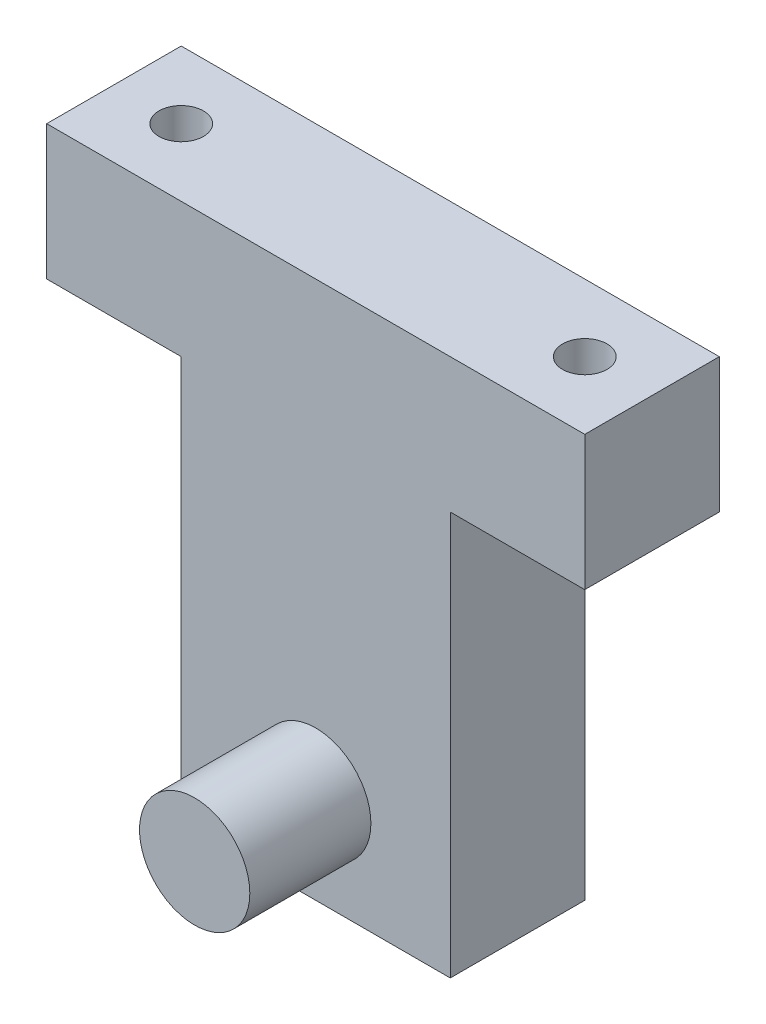
SolidWorks part; units mm, degrees
ref_plane "Спереди" through (0, 0, 0) normal (0, 0, 1) x (1, 0, 0)
ref_plane "Сверху" through (0, 0, 0) normal (0, 1, 0) x (1, 0, 0)
ref_plane "Справа" through (0, 0, 0) normal (1, 0, 0) x (0, 0, -1)
sketch "Эскиз1" plane through (0, 0, 0) normal (0, 0, 1) x (1, 0, 0)
  line L1 (-10, -20) -> (10, -20)
  line L2 (-10, -20) -> (-10, 20)
  line L3 (-10, 20) -> (10, 20)
  line L4 (10, -20) -> (10, 20)
  line L5 (-10, -20) -> (10, 20) construction
  line L6 (-10, 20) -> (10, -20) construction
  line L7 (-10, 20) -> (-20, 20)
  line L8 (-10, 20) -> (-10, 10)
  line L9 (-10, 10) -> (-20, 10)
  line L10 (-20, 20) -> (-20, 10)
  line L11 (10, 20) -> (20, 20)
  line L12 (10, 20) -> (10, 10)
  line L13 (10, 10) -> (20, 10)
  line L14 (20, 20) -> (20, 10)
  point P0 (0, 0)
  point P8 (0, 0)
  point P15 (0, 0)
  dimension "D1" = 20
  dimension "D2" = 40
  dimension "D5" = 10
  dimension "D6" = 10
extrude "Бобышка-Вытянуть5" add sketch "Эскиз1" along normal blind 10 contours L7 L10 L9 L2 | L1 L4 L3 L2 | L14 L11 L4 L13
sketch "Эскиз7" plane through (0, 0, 10) normal (0, 0, 1) x (1, 0, 0)
  line L0 (20, 20) -> (-20, 20) construction
  circle A0 centre (0, -13) radius 4.1
  point P5 (0, 20)
  dimension "D1" = 8.2
  dimension "D2" = 33
extrude "Бобышка-Вытянуть6" add sketch "Эскиз7" along normal blind 9
sketch "Эскиз8" plane through (0, 20, 0) normal (0, 1, 0) x (1, 0, 0)
  line L0 (-20, -10) -> (-20, 0) construction
  line L1 (-10, -10) -> (-20, -10) construction
  line L2 (0, 0) -> (0, -10) construction
  line L3 (20, 0) -> (-20, 0) construction
  line L4 (20, -10) -> (-20, -10) construction
  circle A0 centre (-15, -5) radius 1.65
  circle A1 centre (15, -5) radius 1.65
  point P4 (-20, -5)
  point P7 (-15, -10)
  dimension "D1" = 3.3
extrude "Вырез-Вытянуть1" cut sketch "Эскиз8" against normal blind 10
